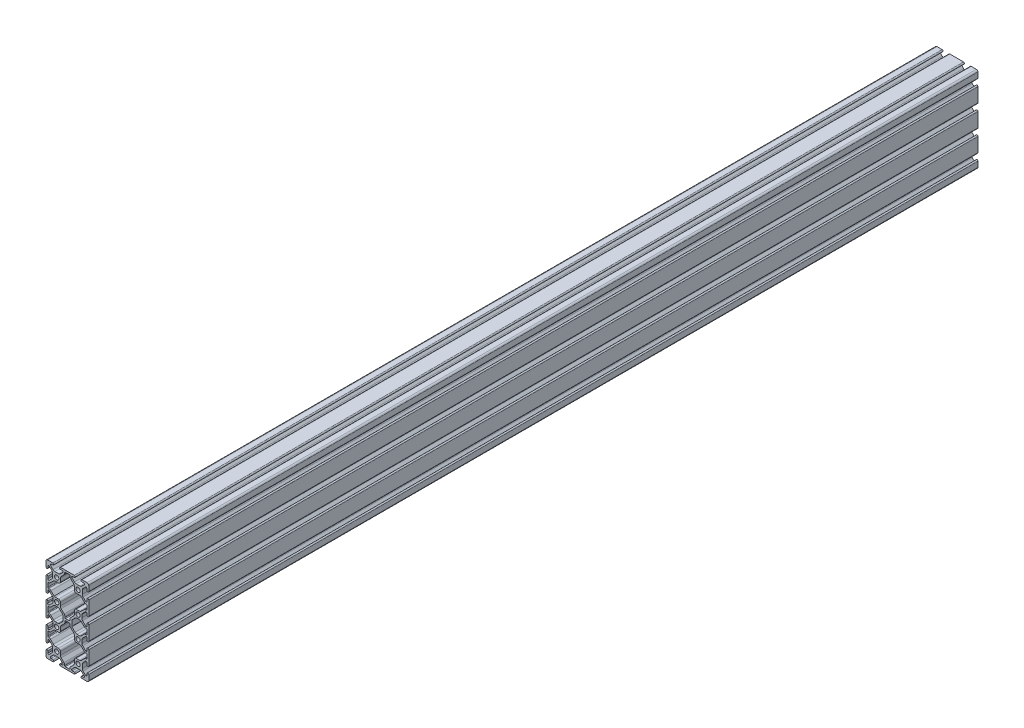
SolidWorks part; units mm, degrees
material "6061 Alloy"
ref_plane "Front Plane" through (0, 0, 0) normal (0, 0, 1) x (1, 0, 0)
ref_plane "Top Plane" through (0, 0, 0) normal (0, 1, 0) x (1, 0, 0)
ref_plane "Right Plane" through (0, 0, 0) normal (1, 0, 0) x (0, 0, -1)
sketch "Sketch1" plane through (0, 0, 0) normal (0, 0, 1) x (1, 0, 0)
  line L0 (-25.6036, 0) -> (0, 0) construction
  line L1 (-8.2025, 43.3108) -> (-5.2383, 46.275)
  line L2 (-25, 3.77) -> (-25, -3.77)
  line L3 (-8.1858, 12.4875) -> (-8.1858, 11.0114)
  line L4 (8.1878, 11.0114) -> (8.1878, 14.5891)
  line L5 (3.7569, 4.9667) -> (7.2705, 8.4802)
  line L6 (14.3225, 16.7991) -> (10.3978, 16.7991)
  line L7 (15.6024, 17.1021) -> (19.2982, 20.7979)
  line L8 (22.1127, 21.7264) -> (21.5397, 21.7264)
  line L9 (-2.3158, 50) -> (2.3158, 50)
  line L10 (22.8749, 26.8568) -> (22.8749, 22.4886)
  line L11 (21.8715, 27.6122) -> (22.1256, 27.6122)
  line L12 (19.7762, 28.7106) -> (16.3874, 32.0994)
  line L13 (13.8398, 33.0305) -> (10.3624, 33.0305)
  line L14 (8.1524, 39.0512) -> (8.1524, 35.2405)
  line L15 (7.2223, 41.2645) -> (4.0122, 44.4746)
  line L16 (3.0895, 47.0978) -> (3.0895, 46.7023)
  line L17 (-22.86, 2.484) -> (-22.86, -2.484)
  line L18 (-5.137, 3.0639) -> (-5.137, -3.0639)
  line L19 (5.137, 3.0639) -> (5.137, -3.0639)
  line L20 (22.86, 2.484) -> (22.86, -2.484)
  line L21 (-5.328, 3.5248) -> (-8.9952, 7.192)
  line L22 (-14.0474, 8.1222) -> (-11.2408, 8.1222)
  line L23 (-16.2931, 7.192) -> (-19.3292, 4.1559)
  line L24 (25, 3.77) -> (25, -3.77)
  line L25 (-22.0978, 3.2462) -> (-21.8437, 3.2462)
  line L26 (-10.3899, 33.0305) -> (-10.3624, 33.0305)
  line L27 (-8.1858, 12.4875) -> (-8.1858, 14.5891)
  line L28 (-8.1524, 39.0512) -> (-8.1524, 35.2405)
  line L29 (-25.6036, -25) -> (3.1162, -25) construction
  line L30 (-12.5, -37.5) -> (-12.5, -51.8721) construction
  line L31 (8.2025, -43.3108) -> (5.2383, -46.275)
  line L32 (-2.8325, -2.6943) -> (-2.8325, -1.8197)
  line L33 (-2.0703, -1.0575) -> (2.0723, -1.0575)
  line L34 (2.8345, -2.6943) -> (2.8345, -1.8197)
  line L35 (-3.7549, -4.9667) -> (-7.2685, -8.4802)
  line L36 (-14.3205, -16.7991) -> (-10.3958, -16.7991)
  line L37 (-15.6004, -17.1021) -> (-19.2962, -20.7979)
  line L38 (-22.1107, -21.7264) -> (-21.5377, -21.7264)
  line L39 (-22.8729, -26.8568) -> (-22.8729, -22.4886)
  line L40 (-22.1107, -27.619) -> (-21.8566, -27.619)
  line L41 (5.328, -3.5248) -> (8.9952, -7.192)
  line L42 (11.2408, -8.1222) -> (14.0474, -8.1222)
  line L43 (16.2931, -7.192) -> (19.3292, -4.1559)
  line L44 (-19.7762, -28.7106) -> (-16.3874, -32.0994)
  line L45 (22.0978, -3.2462) -> (21.8437, -3.2462)
  line L46 (-13.8398, -33.0305) -> (-10.3899, -33.0305)
  line L47 (-7.2223, -41.2645) -> (-4.0122, -44.4746)
  line L48 (5.8948, -47.86) -> (8.0244, -47.86)
  line L49 (-8.0244, 50) -> (-2.3158, 50)
  line L50 (-8.0244, 47.86) -> (-5.8948, 47.86)
  line L51 (0, 47.86) -> (2.3273, 47.86)
  line L52 (-3.0895, -47.0978) -> (-3.0895, -46.7023)
  line L53 (-14.7082, 42.4485) -> (-10.2843, 42.4484)
  line L54 (-16.7975, 43.3108) -> (-19.7617, 46.275)
  line L55 (-19.1052, 47.86) -> (-16.9756, 47.86)
  line L56 (-23.0411, 50) -> (-16.9756, 50)
  line L57 (2.3158, 50) -> (8.0244, 50)
  line L58 (-25, 42.0822) -> (-25, 48.3182)
  line L59 (10.2843, -42.4484) -> (14.7082, -42.4485)
  line L60 (-22.86, 42.0822) -> (-22.86, 44.2118)
  line L61 (-21.1643, 44.6511) -> (-18.3279, 41.8147)
  line L62 (-17.3977, 39.5691) -> (-17.3977, 35.4309)
  line L63 (-18.3279, 33.1853) -> (-21.1271, 30.3861)
  line L64 (-22.86, 31.1039) -> (-22.86, 33.4422)
  line L65 (-25, 33.4422) -> (-25, 29.299)
  line L66 (-25, 21.2197) -> (-25, 29.299)
  line L67 (-25, 17.0404) -> (-25, 21.2197)
  line L68 (-22.8665, 17.0958) -> (-22.8665, 19.4894)
  line L69 (-21.2483, 19.7351) -> (-17.927, 16.4138)
  line L70 (-16.865, 11.3738) -> (-16.865, 14.4803)
  line L71 (-17.7378, 8.7737) -> (-21.0608, 5.4507)
  line L72 (-22.8659, 6.4893) -> (-22.8659, 8.2661)
  line L73 (-25, 3.77) -> (-25, 8.2776)
  line L74 (16.7975, -43.3108) -> (19.7617, -46.275)
  line L75 (19.1052, -47.86) -> (16.9756, -47.86)
  line L76 (16.9756, -50) -> (21.7588, -50)
  line L77 (21.7588, -50) -> (23.0411, -50)
  line L78 (25, -42.0822) -> (25, -48.3182)
  line L79 (22.86, -42.0822) -> (22.86, -44.2118)
  line L80 (21.1643, -44.6511) -> (18.3279, -41.8147)
  line L81 (17.3977, -39.5691) -> (17.3977, -35.4309)
  line L82 (18.3279, -33.1853) -> (21.1271, -30.3861)
  line L83 (25, -33.4422) -> (25, -29.299)
  line L84 (22.86, -31.1039) -> (22.86, -33.4422)
  line L85 (-2.3273, -47.86) -> (0, -47.86)
  line L86 (22.8665, -17.0958) -> (22.8665, -19.4894)
  line L87 (21.2483, -19.7351) -> (17.927, -16.4138)
  line L88 (16.865, -11.3738) -> (16.865, -14.4803)
  line L89 (17.7378, -8.7737) -> (21.0608, -5.4507)
  line L90 (22.8659, -6.4893) -> (22.8659, -8.2661)
  line L91 (25, -21.2197) -> (25, -29.299)
  line L92 (25, -17.0404) -> (25, -21.2197)
  line L93 (25, -3.77) -> (25, -8.2776)
  line L94 (-25, -3.77) -> (-25, -8.2776)
  line L95 (-12.5, 37.5) -> (-12.5, 51.8721) construction
  line L96 (-25.6036, 25) -> (3.1162, 25) construction
  line L97 (-22.8659, -6.4893) -> (-22.8659, -8.2661)
  line L98 (-17.7378, -8.7737) -> (-21.0608, -5.4507)
  line L99 (-16.865, -11.3738) -> (-16.865, -14.4803)
  line L100 (-21.2483, -19.7351) -> (-17.927, -16.4138)
  line L101 (-22.8665, -17.0958) -> (-22.8665, -19.4894)
  line L102 (-25, -17.0404) -> (-25, -21.2197)
  line L103 (-25, -21.2197) -> (-25, -29.299)
  line L104 (-25, -33.4422) -> (-25, -29.299)
  line L105 (-22.86, -31.1039) -> (-22.86, -33.4422)
  line L106 (25, 3.77) -> (25, 8.2776)
  line L107 (25, 17.0404) -> (25, 21.2197)
  line L108 (-18.3279, -33.1853) -> (-21.1271, -30.3861)
  line L109 (-17.3977, -39.5691) -> (-17.3977, -35.4309)
  line L110 (-21.1643, -44.6511) -> (-18.3279, -41.8147)
  line L111 (-22.86, -42.0822) -> (-22.86, -44.2118)
  line L112 (-25, -42.0822) -> (-25, -48.3182)
  line L113 (25, 21.2197) -> (25, 29.299)
  line L114 (2.3158, -50) -> (8.0244, -50)
  line L115 (-23.0411, -50) -> (-16.9756, -50)
  line L116 (22.8659, 6.4893) -> (22.8659, 8.2661)
  line L117 (17.7378, 8.7737) -> (21.0608, 5.4507)
  line L118 (16.865, 11.3738) -> (16.865, 14.4803)
  line L119 (21.2483, 19.7351) -> (17.927, 16.4138)
  line L120 (22.8665, 17.0958) -> (22.8665, 19.4894)
  line L121 (-2.3273, 47.86) -> (0, 47.86)
  line L122 (22.86, 31.1039) -> (22.86, 33.4422)
  line L123 (25, 33.4422) -> (25, 29.299)
  line L124 (-19.1052, -47.86) -> (-16.9756, -47.86)
  line L125 (18.3279, 33.1853) -> (21.1271, 30.3861)
  line L126 (17.3977, 39.5691) -> (17.3977, 35.4309)
  line L127 (21.1643, 44.6511) -> (18.3279, 41.8147)
  line L128 (22.86, 42.0822) -> (22.86, 44.2118)
  line L129 (25, 42.0822) -> (25, 48.3182)
  line L130 (-16.7975, -43.3108) -> (-19.7617, -46.275)
  line L131 (21.7588, 50) -> (23.0411, 50)
  line L132 (16.9756, 50) -> (21.7588, 50)
  line L133 (19.1052, 47.86) -> (16.9756, 47.86)
  line L134 (16.7975, 43.3108) -> (19.7617, 46.275)
  line L135 (10.2843, 42.4484) -> (14.7082, 42.4485)
  line L136 (-14.7082, -42.4485) -> (-10.2843, -42.4484)
  line L137 (-3.0895, 47.0978) -> (-3.0895, 46.7023)
  line L138 (5.8948, 47.86) -> (8.0244, 47.86)
  line L139 (0, -47.86) -> (2.3273, -47.86)
  line L140 (-8.0244, -47.86) -> (-5.8948, -47.86)
  line L141 (-8.0244, -50) -> (-2.3158, -50)
  line L142 (-8.1524, -39.0512) -> (-8.1524, -35.2405)
  line L143 (-8.1858, -12.4875) -> (-8.1858, -14.5891)
  line L144 (-10.3899, -33.0305) -> (-10.3624, -33.0305)
  line L145 (-22.0978, -3.2462) -> (-21.8437, -3.2462)
  line L146 (-16.2931, -7.192) -> (-19.3292, -4.1559)
  line L147 (-14.0474, -8.1222) -> (-11.2408, -8.1222)
  line L148 (-5.328, -3.5248) -> (-8.9952, -7.192)
  line L149 (3.0895, -47.0978) -> (3.0895, -46.7023)
  line L150 (7.2223, -41.2645) -> (4.0122, -44.4746)
  line L151 (8.1524, -39.0512) -> (8.1524, -35.2405)
  line L152 (13.8398, -33.0305) -> (10.3624, -33.0305)
  line L153 (19.7762, -28.7106) -> (16.3874, -32.0994)
  line L154 (-7.2223, 41.2645) -> (-4.0122, 44.4746)
  line L155 (21.8715, -27.6122) -> (22.1256, -27.6122)
  line L156 (22.8749, -26.8568) -> (22.8749, -22.4886)
  line L157 (-2.3158, -50) -> (2.3158, -50)
  line L158 (22.1127, -21.7264) -> (21.5397, -21.7264)
  line L159 (15.6024, -17.1021) -> (19.2982, -20.7979)
  line L160 (-13.8398, 33.0305) -> (-10.3899, 33.0305)
  line L161 (14.3225, -16.7991) -> (10.3978, -16.7991)
  line L162 (22.0978, 3.2462) -> (21.8437, 3.2462)
  line L163 (-19.7762, 28.7106) -> (-16.3874, 32.0994)
  line L164 (16.2931, 7.192) -> (19.3292, 4.1559)
  line L165 (11.2408, 8.1222) -> (14.0474, 8.1222)
  line L166 (5.328, 3.5248) -> (8.9952, 7.192)
  line L167 (3.7569, -4.9667) -> (7.2705, -8.4802)
  line L168 (8.1878, -11.0114) -> (8.1878, -14.5891)
  line L169 (-8.1858, -12.4875) -> (-8.1858, -11.0114)
  line L170 (-8.2025, -43.3108) -> (-5.2383, -46.275)
  line L171 (-22.1107, 27.619) -> (-21.8566, 27.619)
  line L172 (-22.8729, 26.8568) -> (-22.8729, 22.4886)
  line L173 (-22.1107, 21.7264) -> (-21.5377, 21.7264)
  line L174 (-15.6004, 17.1021) -> (-19.2962, 20.7979)
  line L175 (-14.3205, 16.7991) -> (-10.3958, 16.7991)
  line L176 (-3.7549, 4.9667) -> (-7.2685, 8.4802)
  line L177 (2.8345, 2.6943) -> (2.8345, 1.8197)
  line L178 (-2.0703, 1.0575) -> (2.0723, 1.0575)
  line L179 (-2.8325, 2.6943) -> (-2.8325, 1.8197)
  line L180 (25, 0) -> (0, 0) construction
  line L184 (8.2025, 43.3108) -> (5.2383, 46.275)
  arc A0 (-8.1858, 14.5891) -> (-10.3958, 16.7991) centre (-10.3958, 14.5891) ccw
  arc A1 (-8.1524, 35.2405) -> (-10.3624, 33.0305) centre (-10.3624, 35.2405) cw
  arc A2 (10.3978, 16.7991) -> (8.1878, 14.5891) centre (10.3978, 14.5891) ccw
  circle A3 centre (-12.5, 12.5) radius 2.5
  circle A4 centre (-12.5, 37.5) radius 2.5
  arc A5 (7.2705, 8.4802) -> (8.1878, 11.0114) centre (5.0248, 10.7259) ccw
  arc A6 (10.3624, 33.0305) -> (8.1524, 35.2405) centre (10.3624, 35.2405) cw
  arc A7 (14.3225, 16.7991) -> (15.6024, 17.1021) centre (14.2466, 19.974) ccw
  arc A8 (21.5397, 21.7264) -> (19.2982, 20.7979) centre (21.5397, 18.5564) ccw
  arc A9 (22.1127, 21.7264) -> (22.8749, 22.4886) centre (22.1127, 22.4886) ccw
  arc A10 (22.8749, 26.8568) -> (22.1256, 27.6122) centre (22.1127, 26.8501) ccw
  arc A11 (-8.0244, 47.86) -> (-8.0244, 50) centre (-8.0244, 48.93) cw
  arc A12 (19.7762, 28.7106) -> (21.8715, 27.6122) centre (22.1894, 30.7662) ccw
  arc A13 (16.3874, 32.0994) -> (13.8398, 33.0305) centre (13.8398, 29.0797) ccw
  circle A14 centre (12.5, -12.5) radius 2.5
  arc A15 (8.1524, 39.0512) -> (7.2223, 41.2645) centre (4.9767, 39.0188) ccw
  arc A16 (3.0895, 47.0978) -> (2.3273, 47.86) centre (2.3273, 47.0978) ccw
  arc A17 (3.0895, 46.7023) -> (4.0122, 44.4746) centre (6.2399, 46.7023) ccw
  arc A18 (-3.0895, 47.0978) -> (-2.3273, 47.86) centre (-2.3273, 47.0978) cw
  circle A19 centre (12.5, -37.5) radius 2.5
  arc A20 (-3.7549, -4.9667) -> (-2.8325, -2.6943) centre (-5.9826, -2.739) ccw
  arc A21 (-5.137, 3.0639) -> (-5.328, 3.5248) centre (-5.7889, 3.0639) ccw
  arc A22 (-8.9952, 7.192) -> (-11.2408, 8.1222) centre (-11.2408, 4.9464) ccw
  arc A23 (-14.0474, 8.1222) -> (-16.2931, 7.192) centre (-14.0474, 4.9464) ccw
  arc A24 (-21.8437, 3.2462) -> (-19.3292, 4.1559) centre (-21.5569, 6.3836) ccw
  arc A25 (-22.0978, 3.2462) -> (-22.86, 2.484) centre (-22.0978, 2.484) ccw
  arc A26 (-2.0703, -1.0575) -> (-2.8325, -1.8197) centre (-2.0703, -1.8197) ccw
  arc A27 (2.0723, -1.0575) -> (2.8345, -1.8197) centre (2.0723, -1.8197) cw
  arc A28 (3.7569, -4.9667) -> (2.8345, -2.6943) centre (5.9846, -2.739) cw
  arc A29 (-7.2685, -8.4802) -> (-8.1858, -11.0114) centre (-5.0228, -10.7259) ccw
  arc A30 (8.0244, -47.86) -> (8.0244, -50) centre (8.0244, -48.93) cw
  arc A31 (-14.3205, -16.7991) -> (-15.6004, -17.1021) centre (-14.2446, -19.974) ccw
  arc A32 (-21.5377, -21.7264) -> (-19.2962, -20.7979) centre (-21.5377, -18.5564) ccw
  arc A33 (-22.1107, -21.7264) -> (-22.8729, -22.4886) centre (-22.1107, -22.4886) ccw
  arc A34 (-22.8729, -26.8568) -> (-22.1107, -27.619) centre (-22.1107, -26.8568) ccw
  arc A35 (-19.7762, -28.7106) -> (-21.8566, -27.619) centre (-22.1844, -30.772) ccw
  arc A36 (-16.3874, -32.0994) -> (-13.8398, -33.0305) centre (-13.8398, -29.0797) ccw
  arc A37 (5.137, -3.0639) -> (5.328, -3.5248) centre (5.7889, -3.0639) ccw
  arc A38 (8.9952, -7.192) -> (11.2408, -8.1222) centre (11.2408, -4.9464) ccw
  arc A39 (14.0474, -8.1222) -> (16.2931, -7.192) centre (14.0474, -4.9464) ccw
  arc A40 (21.8437, -3.2462) -> (19.3292, -4.1559) centre (21.5569, -6.3836) ccw
  arc A41 (22.0978, -3.2462) -> (22.86, -2.484) centre (22.0978, -2.484) ccw
  arc A42 (5.8948, -47.86) -> (5.2383, -46.275) centre (5.8948, -46.9315) cw
  arc A43 (-8.1524, -39.0512) -> (-7.2223, -41.2645) centre (-4.9767, -39.0188) ccw
  arc A44 (10.2843, -42.4484) -> (8.2025, -43.3108) centre (10.2843, -45.3926) ccw
  arc A45 (16.7975, -43.3108) -> (14.7082, -42.4485) centre (14.7157, -45.3926) ccw
  arc A46 (19.1052, -47.86) -> (19.7617, -46.275) centre (19.1052, -46.9315) ccw
  arc A47 (16.9756, -47.86) -> (16.9756, -50) centre (16.9756, -48.93) ccw
  arc A48 (-5.8948, 47.86) -> (-5.2383, 46.275) centre (-5.8948, 46.9315) cw
  arc A49 (-3.0895, 46.7023) -> (-4.0122, 44.4746) centre (-6.2399, 46.7023) cw
  arc A50 (-10.2843, 42.4484) -> (-8.2025, 43.3108) centre (-10.2843, 45.3926) ccw
  arc A51 (-16.7975, 43.3108) -> (-14.7082, 42.4485) centre (-14.7157, 45.3926) ccw
  arc A52 (-19.1052, 47.86) -> (-19.7617, 46.275) centre (-19.1052, 46.9315) ccw
  arc A53 (-16.9756, 47.86) -> (-16.9756, 50) centre (-16.9756, 48.93) ccw
  arc A54 (-23.0411, 50) -> (-25, 48.3182) centre (-23.0411, 48.0183) ccw
  arc A55 (-25, 42.0822) -> (-22.86, 42.0822) centre (-23.93, 42.0822) ccw
  arc A56 (-21.1643, 44.6511) -> (-22.86, 44.2118) centre (-21.8829, 43.9325) ccw
  arc A57 (-17.3977, 39.5691) -> (-18.3279, 41.8147) centre (-20.5736, 39.5691) ccw
  arc A58 (-18.3279, 33.1853) -> (-17.3977, 35.4309) centre (-20.5736, 35.4309) ccw
  arc A59 (-22.86, 31.1039) -> (-21.1271, 30.3861) centre (-21.8449, 31.1039) ccw
  arc A60 (-22.86, 33.4422) -> (-25, 33.4422) centre (-23.93, 33.4422) ccw
  arc A61 (-25, 17.0404) -> (-22.8665, 17.0958) centre (-23.9321, 17.0236) ccw
  arc A62 (-21.2483, 19.7351) -> (-22.8665, 19.4894) centre (-21.9669, 19.0165) ccw
  arc A63 (-16.865, 14.4803) -> (-17.927, 16.4138) centre (-20.0063, 14.0133) ccw
  arc A64 (-17.7378, 8.7737) -> (-16.865, 11.3738) centre (-20.017, 10.9853) ccw
  arc A65 (-22.8659, 6.4893) -> (-21.0608, 5.4507) centre (-21.9633, 5.97) ccw
  arc A66 (-22.8659, 8.2661) -> (-25, 8.2776) centre (-23.9329, 8.2719) ccw
  arc A67 (23.0411, -50) -> (25, -48.3182) centre (23.0411, -48.0183) ccw
  arc A68 (25, -42.0822) -> (22.86, -42.0822) centre (23.93, -42.0822) ccw
  arc A69 (21.1643, -44.6511) -> (22.86, -44.2118) centre (21.8829, -43.9325) ccw
  arc A70 (17.3977, -39.5691) -> (18.3279, -41.8147) centre (20.5736, -39.5691) ccw
  arc A71 (18.3279, -33.1853) -> (17.3977, -35.4309) centre (20.5736, -35.4309) ccw
  arc A72 (22.86, -31.1039) -> (21.1271, -30.3861) centre (21.8449, -31.1039) ccw
  arc A73 (22.86, -33.4422) -> (25, -33.4422) centre (23.93, -33.4422) ccw
  arc A74 (25, -17.0404) -> (22.8665, -17.0958) centre (23.9321, -17.0236) ccw
  arc A75 (21.2483, -19.7351) -> (22.8665, -19.4894) centre (21.9669, -19.0165) ccw
  arc A76 (16.865, -14.4803) -> (17.927, -16.4138) centre (20.0063, -14.0133) ccw
  arc A77 (17.7378, -8.7737) -> (16.865, -11.3738) centre (20.017, -10.9853) ccw
  arc A78 (22.8659, -6.4893) -> (21.0608, -5.4507) centre (21.9633, -5.97) ccw
  arc A79 (22.8659, -8.2661) -> (25, -8.2776) centre (23.9329, -8.2719) ccw
  arc A80 (-22.8659, -8.2661) -> (-25, -8.2776) centre (-23.9329, -8.2719) cw
  arc A81 (-22.8659, -6.4893) -> (-21.0608, -5.4507) centre (-21.9633, -5.97) cw
  arc A82 (-17.7378, -8.7737) -> (-16.865, -11.3738) centre (-20.017, -10.9853) cw
  arc A83 (-16.865, -14.4803) -> (-17.927, -16.4138) centre (-20.0063, -14.0133) cw
  arc A84 (-21.2483, -19.7351) -> (-22.8665, -19.4894) centre (-21.9669, -19.0165) cw
  arc A85 (-25, -17.0404) -> (-22.8665, -17.0958) centre (-23.9321, -17.0236) cw
  arc A86 (-22.86, -33.4422) -> (-25, -33.4422) centre (-23.93, -33.4422) cw
  arc A87 (-22.86, -31.1039) -> (-21.1271, -30.3861) centre (-21.8449, -31.1039) cw
  arc A88 (-18.3279, -33.1853) -> (-17.3977, -35.4309) centre (-20.5736, -35.4309) cw
  arc A89 (-17.3977, -39.5691) -> (-18.3279, -41.8147) centre (-20.5736, -39.5691) cw
  arc A90 (-21.1643, -44.6511) -> (-22.86, -44.2118) centre (-21.8829, -43.9325) cw
  arc A91 (-25, -42.0822) -> (-22.86, -42.0822) centre (-23.93, -42.0822) cw
  arc A92 (-23.0411, -50) -> (-25, -48.3182) centre (-23.0411, -48.0183) cw
  arc A93 (22.8659, 8.2661) -> (25, 8.2776) centre (23.9329, 8.2719) cw
  arc A94 (22.8659, 6.4893) -> (21.0608, 5.4507) centre (21.9633, 5.97) cw
  arc A95 (17.7378, 8.7737) -> (16.865, 11.3738) centre (20.017, 10.9853) cw
  arc A96 (16.865, 14.4803) -> (17.927, 16.4138) centre (20.0063, 14.0133) cw
  arc A97 (21.2483, 19.7351) -> (22.8665, 19.4894) centre (21.9669, 19.0165) cw
  arc A98 (25, 17.0404) -> (22.8665, 17.0958) centre (23.9321, 17.0236) cw
  arc A99 (22.86, 33.4422) -> (25, 33.4422) centre (23.93, 33.4422) cw
  arc A100 (22.86, 31.1039) -> (21.1271, 30.3861) centre (21.8449, 31.1039) cw
  arc A101 (18.3279, 33.1853) -> (17.3977, 35.4309) centre (20.5736, 35.4309) cw
  arc A102 (17.3977, 39.5691) -> (18.3279, 41.8147) centre (20.5736, 39.5691) cw
  arc A103 (21.1643, 44.6511) -> (22.86, 44.2118) centre (21.8829, 43.9325) cw
  arc A104 (25, 42.0822) -> (22.86, 42.0822) centre (23.93, 42.0822) cw
  arc A105 (23.0411, 50) -> (25, 48.3182) centre (23.0411, 48.0183) cw
  arc A106 (16.9756, 47.86) -> (16.9756, 50) centre (16.9756, 48.93) cw
  arc A107 (19.1052, 47.86) -> (19.7617, 46.275) centre (19.1052, 46.9315) cw
  arc A108 (16.7975, 43.3108) -> (14.7082, 42.4485) centre (14.7157, 45.3926) cw
  arc A109 (10.2843, 42.4484) -> (8.2025, 43.3108) centre (10.2843, 45.3926) cw
  arc A110 (-8.1524, 39.0512) -> (-7.2223, 41.2645) centre (-4.9767, 39.0188) cw
  arc A111 (5.8948, 47.86) -> (5.2383, 46.275) centre (5.8948, 46.9315) ccw
  arc A112 (-16.9756, -47.86) -> (-16.9756, -50) centre (-16.9756, -48.93) cw
  arc A113 (-19.1052, -47.86) -> (-19.7617, -46.275) centre (-19.1052, -46.9315) cw
  arc A114 (-16.7975, -43.3108) -> (-14.7082, -42.4485) centre (-14.7157, -45.3926) cw
  arc A115 (-10.2843, -42.4484) -> (-8.2025, -43.3108) centre (-10.2843, -45.3926) cw
  arc A116 (-3.0895, -46.7023) -> (-4.0122, -44.4746) centre (-6.2399, -46.7023) ccw
  arc A117 (-5.8948, -47.86) -> (-5.2383, -46.275) centre (-5.8948, -46.9315) ccw
  arc A118 (-22.0978, -3.2462) -> (-22.86, -2.484) centre (-22.0978, -2.484) cw
  arc A119 (-21.8437, -3.2462) -> (-19.3292, -4.1559) centre (-21.5569, -6.3836) cw
  arc A120 (-14.0474, -8.1222) -> (-16.2931, -7.192) centre (-14.0474, -4.9464) cw
  arc A121 (-8.9952, -7.192) -> (-11.2408, -8.1222) centre (-11.2408, -4.9464) cw
  arc A122 (-5.137, -3.0639) -> (-5.328, -3.5248) centre (-5.7889, -3.0639) cw
  arc A123 (-3.0895, -47.0978) -> (-2.3273, -47.86) centre (-2.3273, -47.0978) ccw
  arc A124 (3.0895, -46.7023) -> (4.0122, -44.4746) centre (6.2399, -46.7023) cw
  arc A125 (3.0895, -47.0978) -> (2.3273, -47.86) centre (2.3273, -47.0978) cw
  arc A126 (8.1524, -39.0512) -> (7.2223, -41.2645) centre (4.9767, -39.0188) cw
  arc A127 (16.3874, -32.0994) -> (13.8398, -33.0305) centre (13.8398, -29.0797) cw
  arc A128 (19.7762, -28.7106) -> (21.8715, -27.6122) centre (22.1894, -30.7662) cw
  arc A129 (-8.0244, -47.86) -> (-8.0244, -50) centre (-8.0244, -48.93) ccw
  arc A130 (22.8749, -26.8568) -> (22.1256, -27.6122) centre (22.1127, -26.8501) cw
  arc A131 (22.1127, -21.7264) -> (22.8749, -22.4886) centre (22.1127, -22.4886) cw
  arc A132 (21.5397, -21.7264) -> (19.2982, -20.7979) centre (21.5397, -18.5564) cw
  arc A133 (14.3225, -16.7991) -> (15.6024, -17.1021) centre (14.2466, -19.974) cw
  arc A134 (22.0978, 3.2462) -> (22.86, 2.484) centre (22.0978, 2.484) cw
  arc A135 (21.8437, 3.2462) -> (19.3292, 4.1559) centre (21.5569, 6.3836) cw
  arc A136 (14.0474, 8.1222) -> (16.2931, 7.192) centre (14.0474, 4.9464) cw
  arc A137 (8.9952, 7.192) -> (11.2408, 8.1222) centre (11.2408, 4.9464) cw
  arc A138 (5.137, 3.0639) -> (5.328, 3.5248) centre (5.7889, 3.0639) cw
  arc A139 (10.3624, -33.0305) -> (8.1524, -35.2405) centre (10.3624, -35.2405) ccw
  arc A140 (7.2705, -8.4802) -> (8.1878, -11.0114) centre (5.0248, -10.7259) cw
  circle A141 centre (-12.5, -37.5) radius 2.5
  arc A142 (-16.3874, 32.0994) -> (-13.8398, 33.0305) centre (-13.8398, 29.0797) cw
  arc A143 (-19.7762, 28.7106) -> (-21.8566, 27.619) centre (-22.1844, 30.772) cw
  arc A144 (-22.8729, 26.8568) -> (-22.1107, 27.619) centre (-22.1107, 26.8568) cw
  arc A145 (-22.1107, 21.7264) -> (-22.8729, 22.4886) centre (-22.1107, 22.4886) cw
  arc A146 (-21.5377, 21.7264) -> (-19.2962, 20.7979) centre (-21.5377, 18.5564) cw
  arc A147 (-14.3205, 16.7991) -> (-15.6004, 17.1021) centre (-14.2446, 19.974) cw
  arc A148 (8.0244, 47.86) -> (8.0244, 50) centre (8.0244, 48.93) ccw
  circle A149 centre (-12.5, -12.5) radius 2.5
  arc A150 (-7.2685, 8.4802) -> (-8.1858, 11.0114) centre (-5.0228, 10.7259) cw
  arc A151 (3.7569, 4.9667) -> (2.8345, 2.6943) centre (5.9846, 2.739) ccw
  arc A152 (2.0723, 1.0575) -> (2.8345, 1.8197) centre (2.0723, 1.8197) ccw
  arc A153 (-2.0703, 1.0575) -> (-2.8325, 1.8197) centre (-2.0703, 1.8197) cw
  arc A154 (-3.7549, 4.9667) -> (-2.8325, 2.6943) centre (-5.9826, 2.739) cw
  circle A155 centre (12.5, 37.5) radius 2.5
  circle A156 centre (12.5, 12.5) radius 2.5
  arc A157 (10.3978, -16.7991) -> (8.1878, -14.5891) centre (10.3978, -14.5891) cw
  arc A158 (-8.1524, -35.2405) -> (-10.3624, -33.0305) centre (-10.3624, -35.2405) ccw
  arc A159 (-8.1858, -14.5891) -> (-10.3958, -16.7991) centre (-10.3958, -14.5891) cw
  point P0 (-5.137, 0)
  point P2 (-25, 0)
  point P3 (-22.86, 0)
  point P5 (5.137, 0)
  point P511 (22.86, 0)
  dimension "D3" = 6.5
  dimension "D4" = 14.86
  dimension "D6" = 5
  dimension "D7" = 25
  dimension "D10" = 2.21
  dimension "D12" = 2.14
  dimension "D2" = 0.7622
  dimension "D5" = 0.7622
  dimension "D8" = 2.21
  dimension "D11" = 2.21
  dimension "D13" = 2.21
  dimension "D14" = 3.17
  dimension "D15" = 3.17
  dimension "D16" = 3.17
  dimension "D17" = 3.17
  dimension "D9" = 2.14
  dimension "D18" = 100
  dimension "D19" = 50
extrude "Extrude1" add sketch "Sketch1" against normal blind 1039.898
